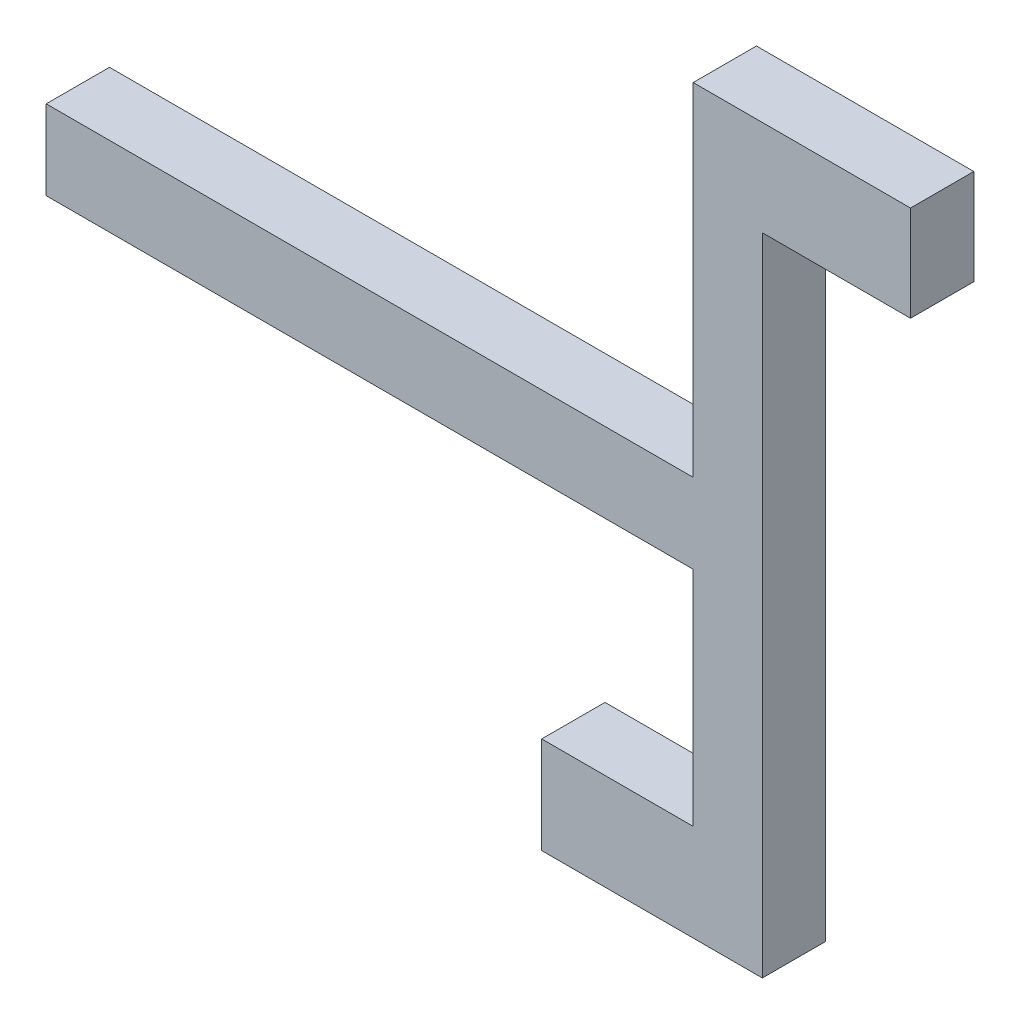
SolidWorks part; units mm, degrees
ref_plane "Спереди" through (0, 0, 0) normal (0, 0, 1) x (1, 0, 0)
ref_plane "Сверху" through (0, 0, 0) normal (0, 1, 0) x (1, 0, 0)
ref_plane "Справа" through (0, 0, 0) normal (1, 0, 0) x (0, 0, -1)
sketch "Эскиз1" plane through (0, 0, 0) normal (0, 0, 1) x (1, 0, 0)
  line L0 (-31.168, 11.7894) -> (275.5857, 11.7894)
  line L1 (275.5857, 11.7894) -> (275.5857, 173.911)
  line L2 (275.5857, 173.911) -> (378.6324, 173.911)
  line L3 (378.6324, 173.911) -> (378.6324, 128.6329)
  line L4 (378.6324, 128.6329) -> (308.3733, 128.6329)
  line L5 (308.3733, 128.6329) -> (308.3733, -177.3846)
  line L6 (308.3733, -177.3846) -> (203.7653, -177.3846)
  line L7 (203.7653, -177.3846) -> (203.7653, -131.5203)
  line L8 (203.7653, -131.5203) -> (275.5857, -131.5203)
  line L9 (275.5857, -131.5203) -> (275.5857, -25.9372)
  line L10 (275.5857, -25.9372) -> (-31.168, -25.9372)
  line L11 (-31.168, -25.9372) -> (-31.168, 11.7894)
  line L12 (327.1091, 128.6329) -> (343.5029, 128.6329)
extrude "Бобышка-Вытянуть1" add sketch "Эскиз1" along normal blind 30 contours L11 L0 L1 L2 L3 L4 L5 L6 L7 L8 L9 L10
